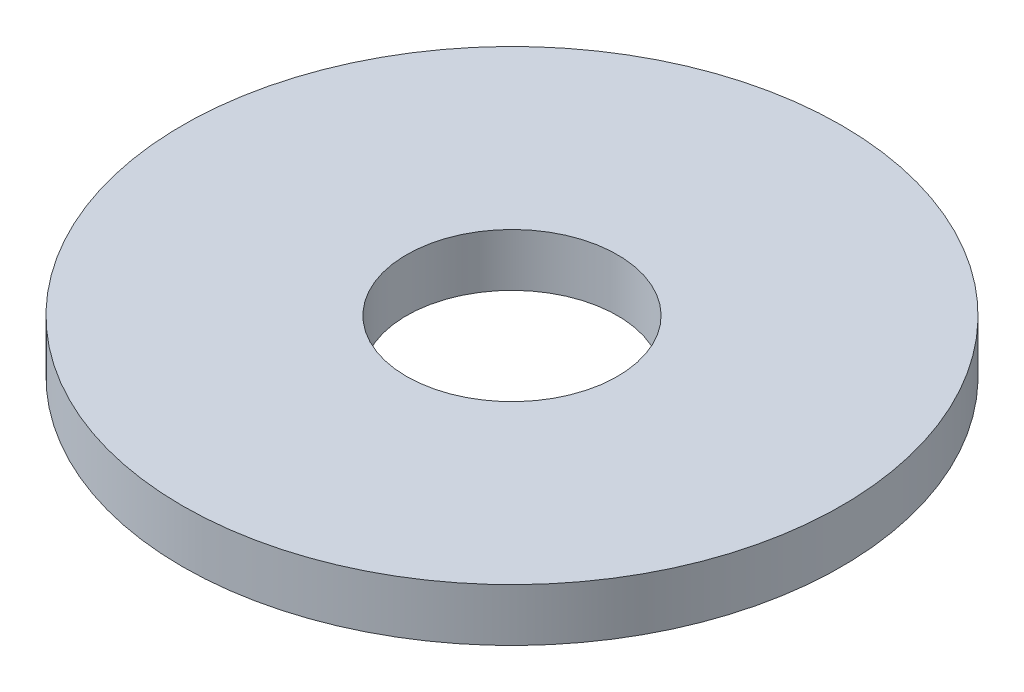
SolidWorks part; units mm, degrees
ref_plane "Front Plane" through (0, 0, 0) normal (0, 0, 1) x (1, 0, 0)
ref_plane "Top Plane" through (0, 0, 0) normal (0, 1, 0) x (1, 0, 0)
ref_plane "Right Plane" through (0, 0, 0) normal (1, 0, 0) x (0, 0, -1)
sketch "Sketch1" plane through (0, 0, 0) normal (0, 1, 0) x (1, 0, 0)
  circle A0 centre (0, 0) radius 1.6
  circle A1 centre (0, 0) radius 5
  dimension "D1" = 3.2
  dimension "D2" = 10
extrude "Boss-Extrude1" add sketch "Sketch1" along normal mid plane 0.8
